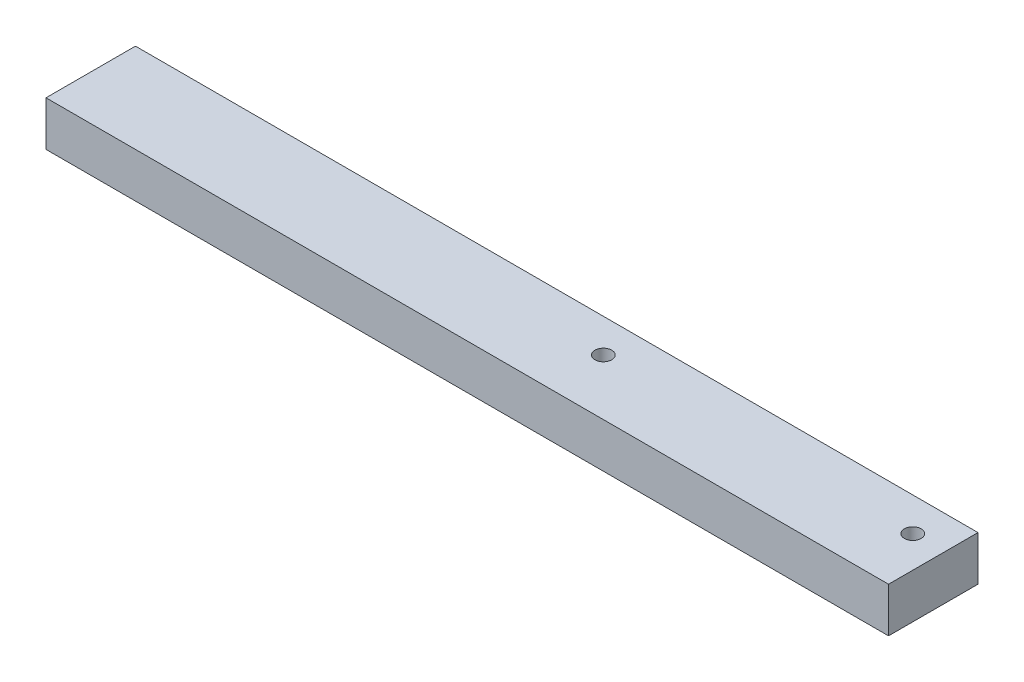
SolidWorks part; units mm, degrees
material "Sapin"
ref_plane "Plan de face" through (0, 0, 0) normal (0, 0, 1) x (1, 0, 0)
ref_plane "Plan de dessus" through (0, 0, 0) normal (0, 1, 0) x (1, 0, 0)
ref_plane "Plan de droite" through (0, 0, 0) normal (1, 0, 0) x (0, 0, -1)
sketch "Esquisse1" plane through (0, 0, 0) normal (0, 1, 0) x (1, 0, 0)
  line L1 (-226, -24) -> (226, -24)
  line L2 (-226, -24) -> (-226, 24)
  line L3 (-226, 24) -> (226, 24)
  line L4 (226, -24) -> (226, 24)
  line L5 (-226, -24) -> (226, 24) construction
  line L6 (-226, 24) -> (226, -24) construction
  point P0 (0, 0)
  dimension "D1" = 452
  dimension "D2" = 48
extrude "Boss.-Extru.1" add sketch "Esquisse1" along normal blind 24
sketch "Esquisse2" plane through (0, 0, 0) normal (0, -1, 0) x (-1, 0, 0)
  line L0 (-226, 24) -> (226, 24) construction
  line L1 (-226, -24) -> (-226, 24) construction
  circle A0 centre (-209, 6) radius 4.5
  circle A1 centre (-43, 6) radius 4.5
  dimension "D4" = 9
  dimension "D1" = 166
  dimension "D2" = 18
  dimension "D3" = 17
extrude "Enlèv. mat.-Extru.1" cut sketch "Esquisse2" against normal through all
